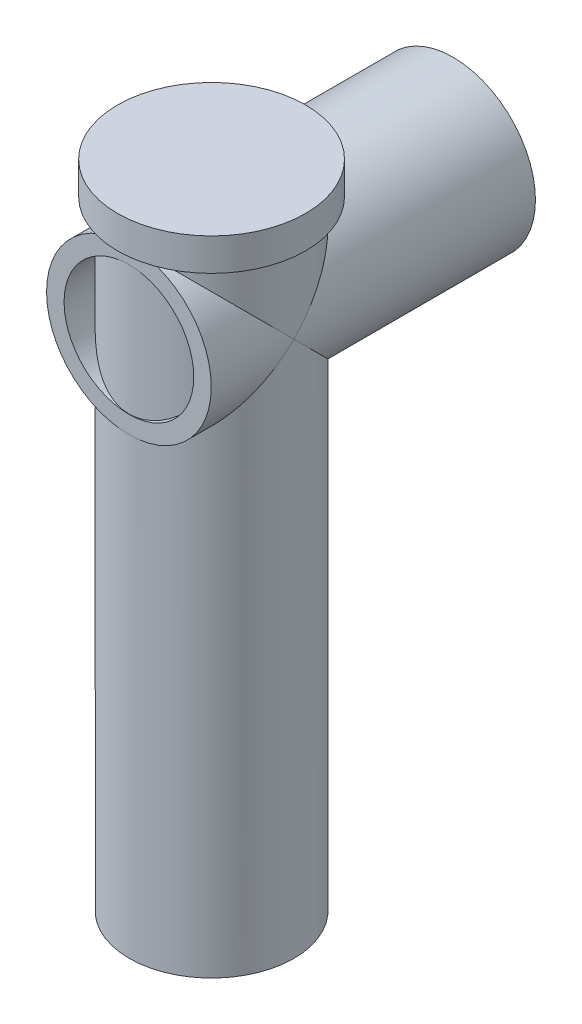
SolidWorks part; units mm, degrees
ref_plane "Alzado" through (0, 0, 0) normal (0, 0, 1) x (1, 0, 0)
ref_plane "Planta" through (0, 0, 0) normal (0, 1, 0) x (1, 0, 0)
ref_plane "Vista lateral" through (0, 0, 0) normal (1, 0, 0) x (0, 0, -1)
sketch "Croquis1" plane through (0, 0, 0) normal (0, 0, 1) x (1, 0, 0)
  circle A0 centre (0, 0) radius 12.7
  circle A1 centre (0, 0) radius 10
extrude "Saliente-Extruir1" add sketch "Croquis1" along normal blind 50
ref_plane "Plano1" through (0, -12.7, 0) normal (0, 1, 0) x (1, 0, 0)
sketch "Croquis2" plane through (0, -12.7, 0) normal (0, 1, 0) x (1, 0, 0)
  circle A0 centre (0, -37.25) radius 12.7
extrude "Saliente-Extruir2" add sketch "Croquis2" against normal blind 70 and the other way blind 25.4
sketch "Croquis3" plane through (0, -12.7, 0) normal (0, 1, 0) x (1, 0, 0)
  circle A0 centre (0, -37.25) radius 10
extrude "Cortar-Extruir1" cut sketch "Croquis3" along normal through all both and the other way through all
sketch "Croquis4" plane through (0, 0, 0) normal (0, 0, 1) x (1, 0, 0)
  circle A0 centre (0, 0) radius 10
extrude "Cortar-Extruir2" cut sketch "Croquis4" along normal blind 42
ref_plane "Plano2" through (0, 12.7, 0) normal (0, 1, 0) x (1, 0, 0)
sketch "Croquis5" plane through (0, 12.7, 0) normal (0, 1, 0) x (1, 0, 0)
  circle A0 centre (0, -37.25) radius 14.5
extrude "Saliente-Extruir4" add sketch "Croquis5" along normal blind 5 separate body
